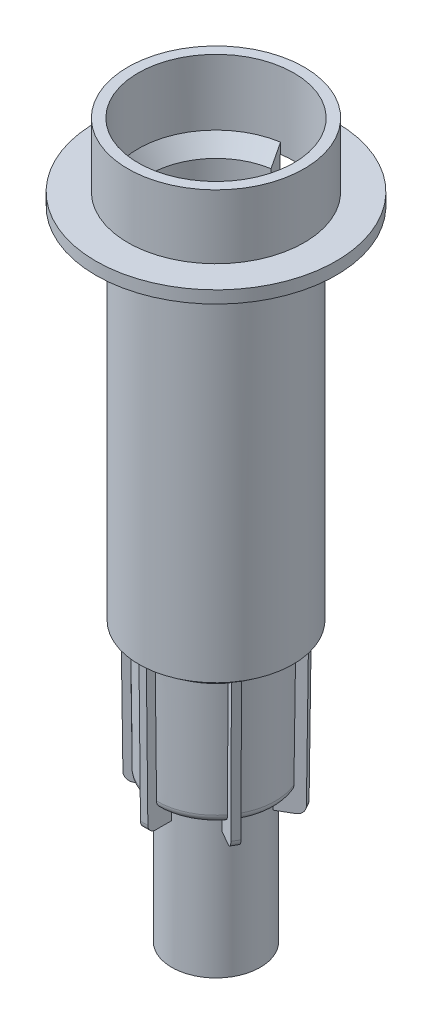
SolidWorks part; units mm, degrees
ref_plane "Front Plane" through (0, 0, 0) normal (0, 0, 1) x (1, 0, 0)
ref_plane "Top Plane" through (0, 0, 0) normal (0, 1, 0) x (1, 0, 0)
ref_plane "Right Plane" through (0, 0, 0) normal (1, 0, 0) x (0, 0, -1)
sketch "Sketch3" plane through (0, 0, 0) normal (1, 0, 0) x (0, 0, -1)
  line L0 (0, 0) -> (0, 87) construction
  line L1 (5.4, 0) -> (5.4, 17.5)
  line L2 (5.4, 17.5) -> (6.2501, 17.5)
  line L3 (7.25, 18.4893) -> (7.4, 32.5)
  line L4 (7.4, 32.5) -> (9.4, 34)
  line L5 (9.4, 34) -> (9.4, 77.7)
  line L6 (9.4, 77.7) -> (14.65, 77.7)
  line L7 (14.65, 77.7) -> (14.65, 79.2)
  line L8 (14.65, 79.2) -> (10.75, 79.2)
  line L9 (10.75, 79.2) -> (10.75, 87)
  line L10 (10.75, 87) -> (9.5, 87)
  line L11 (9.5, 87) -> (9.5, 79)
  line L12 (9.5, 79) -> (8.1, 77)
  line L13 (8.1, 77) -> (8.1, 34)
  line L14 (8.1, 34) -> (6, 32.425)
  line L15 (2.85, 11.5) -> (2.1, 11.5)
  line L16 (2.85, 11.5) -> (3.0625, 13)
  line L17 (3.75, 13) -> (3.75, 2)
  line L18 (3.75, 2) -> (4.4, 0)
  line L19 (4.4, 0) -> (5.4, 0)
  line L20 (2.1, 11.5) -> (2.5391, 14.6)
  line L21 (2.5391, 14.6) -> (5.8563, 19)
  line L22 (5.8563, 19) -> (6, 32.425)
  line L23 (3.0625, 13) -> (3.75, 13)
  arc A0 (6.2501, 17.5) -> (7.25, 18.4893) centre (6.2501, 18.5) ccw
  circle A1 centre (0, 14.5) radius 2.5 construction
  dimension "D20" = 1
  dimension "D22" = 5
  dimension "D23" = 70
  dimension "D1" = 1.5
  dimension "D2" = 21.5
  dimension "D3" = 29.3
  dimension "D4" = 87
  dimension "D5" = 7.8
  dimension "D6" = 19
  dimension "D7" = 18.8
  dimension "D8" = 8
  dimension "D9" = 10
  dimension "D10" = 16.2
  dimension "D11" = 14.8
  dimension "D12" = 14.5
  dimension "D13" = 1.5
  dimension "D14" = 32.5
  dimension "D15" = 7.5
  dimension "D16" = 2
  dimension "D17" = 1
  dimension "D18" = 10.8
  dimension "D19" = 11.5
  dimension "D21" = 17.5
  dimension "D24" = 53
  dimension "D25" = 12
  dimension "D26" = 68
  dimension "D27" = 4.2
  dimension "D28" = 13
  dimension "D29" = 0.75
  dimension "D30" = 4.4
revolve "Revolve2" add sketch "Sketch3" angle 360 about L0
sketch "Sketch4" plane through (0, 0, 0) normal (1, 0, 0) x (0, 0, -1)
  line L0 (8.5, 34.3) -> (8.3089, 16.4464)
  line L1 (7.3523, 15.5) -> (3.2176, 15.5)
  line L5 (7.25, 18.4893) -> (7.4, 32.5) construction
  line L7 (0, 0) -> (0, 30.7767) construction
  line L8 (8.5, 34.3) -> (6, 32.425)
  line L12 (6, 32.425) -> (5.8563, 19)
  line L16 (5.8563, 19) -> (3.2176, 15.5)
  arc A0 (8.3089, 16.4464) -> (7.3523, 15.5) centre (7.3523, 16.4567) cw
  dimension "D2" = 17
extrude "Boss-Extrude2" add sketch "Sketch4" along normal blind 0.9
pattern_circular "CirPattern1" count 6 over 360 about axis through (0, 0, 0) along (0, 1, 0) of "Boss-Extrude2"
sketch "Sketch6" plane through (0, 0, 0) normal (1, 0, 0) x (0, 0, -1)
  line L0 (0, 0) -> (0, 97.1318) construction
  line L3 (8.1, 77) -> (8.1, 72.4)
  line L4 (9.5, 73.6) -> (8.1, 72.4)
  line L8 (9.5, 79) -> (8.1, 77)
  line L11 (9.5, 73.6) -> (9.5, 79)
revolve "Cut-Revolve2" cut sketch "Sketch6" angle 18.3 mid plane about L0
